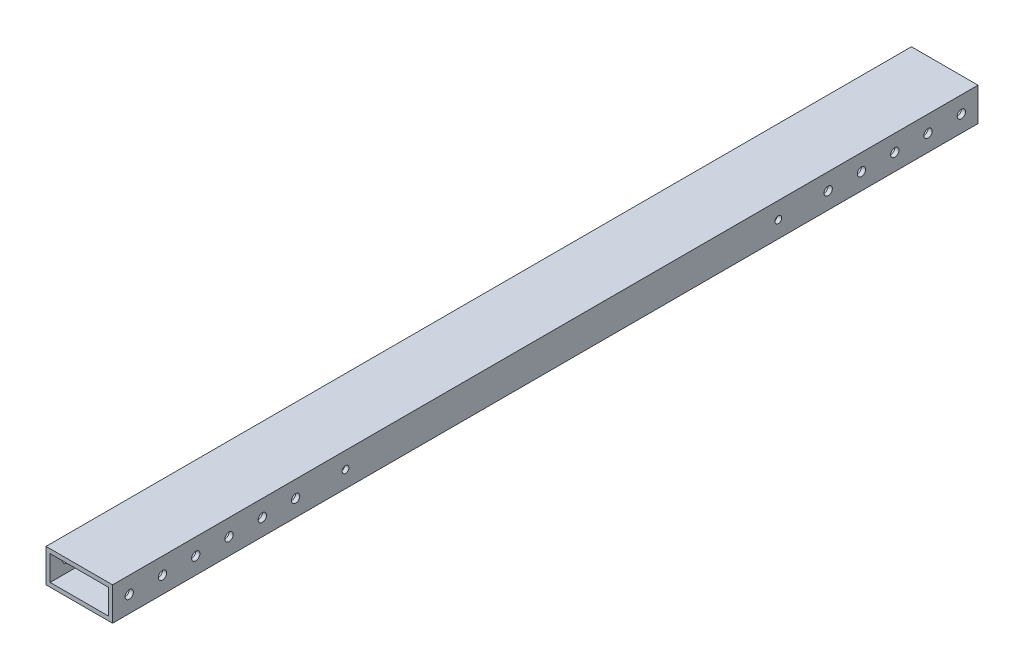
SolidWorks part; units mm, degrees
material "6061 Alloy"
ref_plane "Front Plane" through (0, 0, 0) normal (0, 0, 1) x (1, 0, 0)
ref_plane "Top Plane" through (0, 0, 0) normal (0, 1, 0) x (1, 0, 0)
ref_plane "Right Plane" through (0, 0, 0) normal (1, 0, 0) x (0, 0, -1)
sketch "Sketch1" plane through (0, 0, 0) normal (0, 0, 1) x (1, 0, 0)
  line L0 (-22.225, 9.525) -> (22.225, 9.525)
  line L2 (-25.4, 12.7) -> (25.4, 12.7)
  line L3 (-25.4, 12.7) -> (-25.4, -12.7)
  line L4 (-25.4, -12.7) -> (25.4, -12.7)
  line L5 (25.4, 12.7) -> (25.4, -12.7)
  line L10 (22.225, 9.525) -> (22.225, -9.525)
  line L11 (-22.225, -9.525) -> (22.225, -9.525)
  line L12 (-22.225, 9.525) -> (-22.225, -9.525)
  point P12 (0, 12.7)
  point P14 (25.4, 0)
  dimension "Wall Thickness" = 3.175
  dimension "Outside Width" = 50.8
  dimension "Outside Height" = 25.4
  dimension "Inside Height" = 19.05
  dimension "Inside Width" = 44.45
sketch "Sketch2" plane through (0, 0, 0) normal (1, 0, 0) x (0, 0, -1)
  line L0 (330.2, 0) -> (-330.2, 0)
  point P4 (0, 0)
  point P7 (-330.2, 0)
  point P10 (330.2, 0)
  dimension "Length" = 660.4
sketch "Sketch3" plane through (0, 0, 0) normal (0, 0, 1) x (1, 0, 0)
  line L21 (25.4, 12.7) -> (-25.4, 12.7)
  line L22 (25.4, -12.7) -> (25.4, 12.7)
  line L23 (-25.4, -12.7) -> (25.4, -12.7)
  line L24 (-25.4, 12.7) -> (-25.4, -12.7)
  line L25 (25.4, 12.7) -> (-25.4, 12.7)
  line L26 (25.4, -12.7) -> (25.4, 12.7)
  line L27 (-25.4, -12.7) -> (25.4, -12.7)
  line L28 (-25.4, 12.7) -> (-25.4, -12.7)
  line L29 (22.225, 9.525) -> (-22.225, 9.525)
  line L30 (22.225, -9.525) -> (22.225, 9.525)
  line L31 (-22.225, -9.525) -> (22.225, -9.525)
  line L32 (-22.225, 9.525) -> (-22.225, -9.525)
  line L33 (22.225, 9.525) -> (-22.225, 9.525)
  line L34 (22.225, -9.525) -> (22.225, 9.525)
  line L35 (-22.225, -9.525) -> (22.225, -9.525)
  line L36 (-22.225, 9.525) -> (-22.225, -9.525)
  dimension "D1" = 0
  dimension "D2" = 0
extrude "Boss-Extrude1" add sketch "Sketch3" along normal up to vertex (330.2 mm away) and the other way up to vertex (330.2 mm away) up to point (0, 0, 330.2) other way up to point (0, 0, -330.2)
sketch "Drawing Reference" plane through (0, 0, 0) normal (1, 0, 0) x (0, 0, -1)
  line L0 (-330.2, 0) -> (330.2, 0) construction
  line L1 (0, -12.7) -> (0, 12.7) construction
  line L2 (-330.2, -12.7) -> (330.2, -12.7) construction
  line L5 (-330.2, 12.7) -> (330.2, 12.7) construction
  point P7 (-293.624, 0)
  point P8 (293.624, 0)
  dimension "D1" = 36.576
sketch "Sketch5" plane through (25.4, 0, 0) normal (1, 0, 0) x (0, 0, -1)
  line L2 (-266.7, 0) -> (-241.3, 0)
  line L3 (-241.3, 0) -> (-215.9, 0)
  line L4 (-215.9, 0) -> (-190.5, 0)
  line L5 (-317.5, 0) -> (-330.2, 0)
  line L6 (-330.2, -12.7) -> (-330.2, 12.7) construction
  line L7 (-317.5, 0) -> (-292.1, 0)
  line L8 (-292.1, 0) -> (-266.7, 0)
sketch "Sketch8" plane through (25.4, 0, 0) normal (1, 0, 0) x (0, 0, -1)
  line L0 (330.2, 0) -> (292.1, 0)
  line L1 (330.2, -12.7) -> (330.2, 12.7) construction
  line L2 (292.1, 0) -> (266.7, 0)
  line L3 (266.7, 0) -> (241.3, 0)
  line L4 (241.3, 0) -> (215.9, 0)
  line L5 (330.2, 0) -> (317.5, 0)
hole_wizard "1/4 (0.25) Diameter Hole3" positions "Sketch12" profile "Sketch13" hole size "1/4" standard "ANSI Inch" end condition through all
sketch "Sketch12" plane through (-25.4, 0, 0) normal (-1, 0, 0) x (0, 0, 1)
  point P4 (-317.5, 0)
sketch "Sketch13" plane through (-25.4, 0, -317.5) normal (0, 1, 0) x (0, 0, 1)
  line L0 (0, 0) -> (0, 50.8)
  line L1 (0, 50.8) -> (3.175, 50.8)
  line L2 (3.175, 50.8) -> (3.175, 0)
  line L5 (3.175, 0) -> (0, 0)
  line L11 (0, -6.35) -> (0, 107.95) construction
  dimension "Thru Hole Dia." = 6.35
  dimension "Thru Hole Depth" = 50.8
hole_wizard "1/4 (0.25) Diameter Hole4" positions "Sketch14" profile "Sketch15" hole size "1/4" standard "ANSI Inch" end condition through all
sketch "Sketch14" plane through (-25.4, 0, 0) normal (-1, 0, 0) x (0, 0, 1)
  point P0 (292.1, 0)
  point P3 (317.5, 0)
sketch "Sketch15" plane through (-25.4, 0, 292.1) normal (0, 1, 0) x (0, 0, 1)
  line L0 (0, 0) -> (0, 50.8)
  line L1 (0, 50.8) -> (3.175, 50.8)
  line L2 (3.175, 50.8) -> (3.175, 0)
  line L5 (3.175, 0) -> (0, 0)
  line L11 (0, -6.35) -> (0, 107.95) construction
  dimension "Thru Hole Dia." = 6.35
  dimension "Thru Hole Depth" = 50.8
hole_wizard "1/4 (0.25) Diameter Hole5" positions "Sketch17" profile "Sketch18" hole size "1/4" standard "ANSI Inch" end condition through all
sketch "Sketch17" plane through (25.4, 0, 0) normal (1, 0, 0) x (0, 0, -1)
  point P0 (292.1, 0)
  point P3 (266.7, 0)
sketch "Sketch18" plane through (25.4, 0, -292.1) normal (0, 1, 0) x (0, 0, -1)
  line L0 (0, 0) -> (0, 50.8)
  line L1 (0, 50.8) -> (3.175, 50.8)
  line L2 (3.175, 50.8) -> (3.175, 0)
  line L5 (3.175, 0) -> (0, 0)
  line L11 (0, -6.35) -> (0, 107.95) construction
  dimension "Thru Hole Dia." = 6.35
  dimension "Thru Hole Depth" = 50.8
hole_wizard "1/4 (0.25) Diameter Hole6" positions "Sketch19" profile "Sketch20" hole size "1/4" standard "ANSI Inch" end condition through all
sketch "Sketch19" plane through (25.4, 0, 0) normal (1, 0, 0) x (0, 0, -1)
  point P0 (215.9, 0)
  point P3 (241.3, 0)
sketch "Sketch20" plane through (25.4, 0, -215.9) normal (0, 1, 0) x (0, 0, -1)
  line L0 (0, 0) -> (0, 50.8)
  line L1 (0, 50.8) -> (3.175, 50.8)
  line L2 (3.175, 50.8) -> (3.175, 0)
  line L5 (3.175, 0) -> (0, 0)
  line L11 (0, -6.35) -> (0, 107.95) construction
  dimension "Thru Hole Dia." = 6.35
  dimension "Thru Hole Depth" = 50.8
hole_wizard "1/4 (0.25) Diameter Hole7" positions "Sketch21" profile "Sketch22" hole size "1/4" standard "ANSI Inch" end condition through all
sketch "Sketch21" plane through (25.4, 0, 0) normal (1, 0, 0) x (0, 0, -1)
  point P0 (-190.5, 0)
  point P3 (-215.9, 0)
sketch "Sketch22" plane through (25.4, 0, 190.5) normal (0, 1, 0) x (0, 0, -1)
  line L0 (0, 0) -> (0, 50.8)
  line L1 (0, 50.8) -> (3.175, 50.8)
  line L2 (3.175, 50.8) -> (3.175, 0)
  line L5 (3.175, 0) -> (0, 0)
  line L11 (0, -6.35) -> (0, 107.95) construction
  dimension "Thru Hole Dia." = 6.35
  dimension "Thru Hole Depth" = 50.8
hole_wizard "1/4 (0.25) Diameter Hole8" positions "Sketch23" profile "Sketch24" hole size "1/4" standard "ANSI Inch" end condition through all
sketch "Sketch23" plane through (25.4, 0, 0) normal (1, 0, 0) x (0, 0, -1)
  point P0 (-266.7, 0)
  point P3 (-241.3, 0)
sketch "Sketch24" plane through (25.4, 0, 266.7) normal (0, 1, 0) x (0, 0, -1)
  line L0 (0, 0) -> (0, 50.8)
  line L1 (0, 50.8) -> (3.175, 50.8)
  line L2 (3.175, 50.8) -> (3.175, 0)
  line L5 (3.175, 0) -> (0, 0)
  line L11 (0, -6.35) -> (0, 107.95) construction
  dimension "Thru Hole Dia." = 6.35
  dimension "Thru Hole Depth" = 50.8
sketch "Sketch25" plane through (25.4, 0, 0) normal (1, 0, 0) x (0, 0, -1)
  line L0 (-190.5, 0) -> (-152.4, 0)
  line L1 (215.9, 0) -> (177.8, 0)
hole_wizard "13/64 (0.20313) Diameter Hole1" positions "Sketch26" profile "Sketch27" hole size "13/64" standard "ANSI Inch" end condition through all
sketch "Sketch26" plane through (25.4, 0, 0) normal (1, 0, 0) x (0, 0, -1)
  point P0 (-152.4, 0)
  point P3 (177.8, 0)
sketch "Sketch27" plane through (25.4, 0, 152.4) normal (0, 1, 0) x (0, 0, -1)
  line L0 (0, 0) -> (0, 50.8)
  line L1 (0, 50.8) -> (2.5798, 50.8)
  line L2 (2.5798, 50.8) -> (2.5798, 0)
  line L5 (2.5798, 0) -> (0, 0)
  line L11 (0, -6.35) -> (0, 107.95) construction
  dimension "Thru Hole Dia." = 5.1595
  dimension "Thru Hole Depth" = 50.8
hole_wizard "1/2 (0.5) Diameter Hole1" positions "Sketch33" profile "Sketch34" hole size "1/2" standard "ANSI Inch"
sketch "Sketch33" plane through (-25.4, 0, 0) normal (-1, 0, 0) x (0, 0, 1)
  point P0 (-146.05, 0)
  point P3 (120.65, 0)
  point P12 (-127, 0)
  point P14 (-101.6, 0)
sketch "Sketch34" plane through (-25.4, 0, -146.05) normal (0, 1, 0) x (0, 0, 1)
  line L0 (0, 0) -> (0, 10.1655)
  line L1 (0, 10.1655) -> (6.35, 6.35)
  line L2 (6.35, 6.35) -> (6.35, 0)
  line L5 (6.35, 0) -> (0, 0)
  line L10 (0, 10.1655) -> (-6.35, 6.35) construction
  line L11 (0, -6.35) -> (0, 107.95) construction
  dimension "Hole Dia." = 12.7
  dimension "Hole Depth" = 6.35
  dimension "Drill Angle" = 118
equation "\"D1@Drawing Reference\"=\"Outside Width@Sketch1\" * 0.72"
